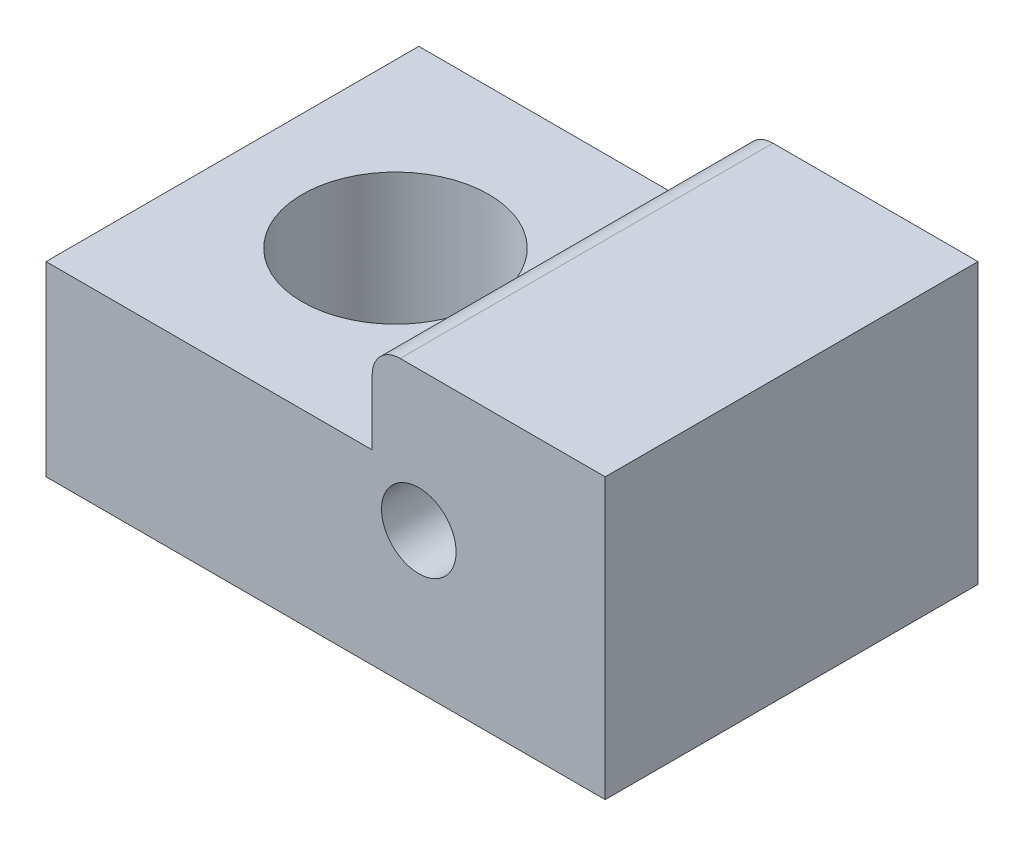
SolidWorks part; units mm, degrees
material "ABS"
ref_plane "前视基准面" through (0, 0, 0) normal (0, 0, 1) x (1, 0, 0)
ref_plane "上视基准面" through (0, 0, 0) normal (0, 1, 0) x (1, 0, 0)
ref_plane "右视基准面" through (0, 0, 0) normal (1, 0, 0) x (0, 0, -1)
sketch "草图1" plane through (0, 0, 0) normal (0, 0, 1) x (1, 0, 0)
  line L0 (-41.3745, 0) -> (59.1904, 0) construction
  line L1 (8, 15) -> (30, 15)
  line L2 (-30, 5) -> (-30, -15)
  line L3 (-30, -15) -> (30, -15)
  line L4 (30, 15) -> (30, -15)
  line L5 (-10, 5) -> (30, -15) construction
  line L6 (-30, -15) -> (30, 15) construction
  line L10 (-30, 5) -> (5, 5)
  line L11 (5, 12) -> (5, 5)
  circle A0 centre (10, 0) radius 4
  arc A1 (8, 15) -> (5, 12) centre (8, 12) ccw
  point P0 (0, 0)
  point P15 (5, 15)
  dimension "D4" = 8
  dimension "D7" = 3
  dimension "D1" = 60
  dimension "D2" = 30
  dimension "D3" = 20
  dimension "D5" = 35
  dimension "D6" = 10
extrude "凸台-拉伸1" add sketch "草图1" along normal blind 40
sketch "草图2" plane through (0, 0, 0) normal (0, 1, 0) x (1, 0, 0)
  line L0 (-12.5, 0) -> (-12.5, -40) construction
  line L1 (5, 0) -> (-30, 0) construction
  line L2 (5, -40) -> (-30, -40) construction
  circle A0 centre (-12.5, -20) radius 10
  dimension "D1" = 20
extrude "切除-拉伸1" cut sketch "草图2" against normal blind 40 from surface at 5 starting at face at (-12.5, 5, 20)
